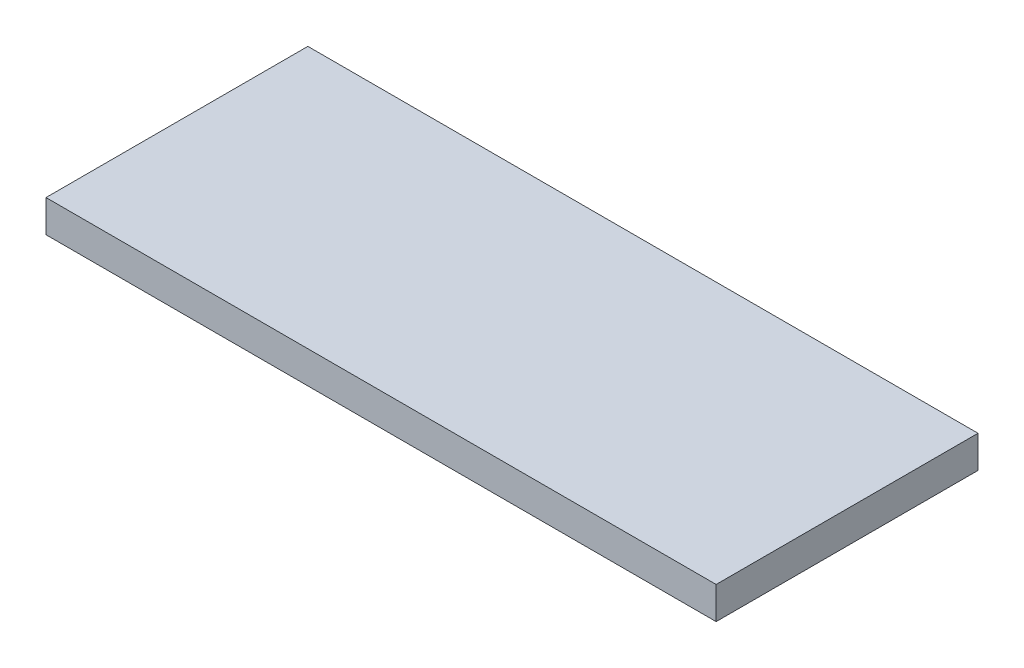
SolidWorks part; units mm, degrees
material "Plain Carbon Steel"
ref_plane "Front Plane" through (0, 0, 0) normal (0, 0, 1) x (1, 0, 0)
ref_plane "Top Plane" through (0, 0, 0) normal (0, 1, 0) x (1, 0, 0)
ref_plane "Right Plane" through (0, 0, 0) normal (1, 0, 0) x (0, 0, -1)
sketch "Sketch1" plane through (0, 0, 0) normal (0, 1, 0) x (1, 0, 0)
  line L1 (-32.5, -12.7) -> (32.5, -12.7)
  line L2 (-32.5, -12.7) -> (-32.5, 12.7)
  line L3 (-32.5, 12.7) -> (32.5, 12.7)
  line L4 (32.5, -12.7) -> (32.5, 12.7)
  line L5 (0, 12.7) -> (0, -12.7) construction
  line L6 (-32.5, 0) -> (32.5, 0) construction
  point P0 (0, 0)
  dimension "D1" = 25.4
  dimension "D2" = 65
extrude "Boss-Extrude1" add sketch "Sketch1" along normal blind 3.125
